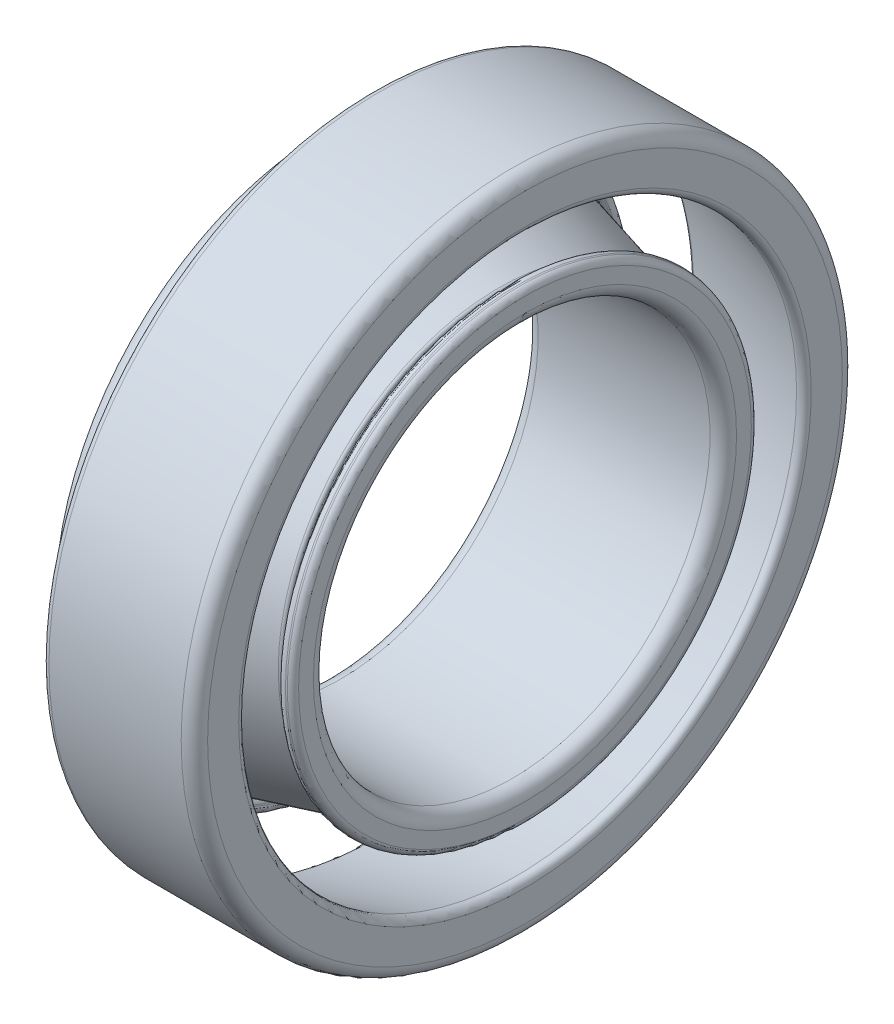
SolidWorks part; units mm, degrees
ref_plane "Front Plane" through (0, 0, 0) normal (0, 0, 1) x (1, 0, 0)
ref_plane "Top Plane" through (0, 0, 0) normal (0, 1, 0) x (1, 0, 0)
ref_plane "Right Plane" through (0, 0, 0) normal (1, 0, 0) x (0, 0, -1)
sketch "Sketch1" plane through (0, 0, 0) normal (0, 0, 1) x (1, 0, 0)
  line L0 (0, 0) -> (105.028, 0) construction
  line L1 (0, 48) -> (0, 43.2987)
  line L2 (-1.2522, 42.3311) -> (-22.2522, 47.8051)
  line L3 (-23, 49) -> (-23, 48.7727)
  line L4 (-22, 50) -> (-2, 50)
  line L5 (-11.7522, 45.0681) -> (-32.0851, -32.935) construction
  line L6 (-24.2703, 38.651) -> (-3.9596, 33.3567)
  line L7 (-2.2344, 34.3685) -> (-2.1876, 34.5483)
  line L8 (-0.9677, 35.2637) -> (-0.7478, 35.2064)
  line L9 (0, 34.2387) -> (0, 32)
  line L10 (-2, 30) -> (-28, 30)
  line L11 (-30, 32) -> (-30, 40.2433)
  line L12 (-27.4955, 42.1786) -> (-25.9506, 41.7759)
  line L13 (-25.2352, 40.556) -> (-25.2821, 40.3762)
  arc A0 (0, 48) -> (-2, 50) centre (-2, 48) ccw
  arc A1 (-23, 48.7727) -> (-22.2522, 47.8051) centre (-22, 48.7727) ccw
  arc A2 (0, 43.2987) -> (-1.2522, 42.3311) centre (-1, 43.2987) cw
  arc A3 (-23, 49) -> (-22, 50) centre (-22, 49) cw
  arc A4 (-25.7235, 40.0042) -> (-24.8106, 38.4474) centre (-25.6388, 39.0078) ccw
  arc A5 (-3.5876, 32.9153) -> (-2.0308, 33.8282) centre (-2.5912, 33) ccw
  arc A6 (0, 32) -> (-2, 30) centre (-2, 32) cw
  arc A7 (-28, 30) -> (-30, 32) centre (-28, 32) cw
  arc A8 (-30, 40.2433) -> (-27.4955, 42.1786) centre (-28, 40.2433) cw
  arc A9 (-0.7478, 35.2064) -> (0, 34.2387) centre (-1, 34.2387) cw
  arc A10 (-2.1876, 34.5483) -> (-0.9677, 35.2637) centre (-1.2199, 34.296) cw
  arc A11 (-25.9506, 41.7759) -> (-25.2352, 40.556) centre (-26.2029, 40.8083) cw
  arc A12 (-2.0308, 33.8282) -> (-2.2344, 34.3685) centre (-1.7506, 34.2424) cw
  arc A13 (-3.5876, 32.9153) -> (-3.9596, 33.3567) centre (-4.0858, 32.8729) ccw
  arc A14 (-24.8106, 38.4474) -> (-24.2703, 38.651) centre (-24.3964, 38.1672) cw
  arc A15 (-25.7235, 40.0042) -> (-25.2821, 40.3762) centre (-25.7659, 40.5024) ccw
  point P9 (-23.5, 0)
  point P10 (0, 0)
  point P13 (0, 50)
  point P16 (-23, 50)
  point P21 (-23, 48)
  point P31 (-14.115, 36.0039)
  point P35 (-23, 50)
  point P38 (0, 30)
  point P41 (-30, 30)
  point P46 (0, 35.0115)
  point P49 (-1.9353, 35.5159)
  point P54 (-2.3389, 33.9677)
  dimension "D5" = 2
  dimension "D6" = 1
  dimension "D9" = 2
  dimension "D10" = 2
  dimension "D15" = 1
  dimension "D16" = 1
  dimension "D17" = 2
  dimension "D18" = 1
  dimension "D19" = 0.5
  dimension "D1" = 23
  dimension "D2" = 50
  dimension "D3" = 23.5
  dimension "D4" = 48
  dimension "D7" = 1.6
  dimension "D8" = 2
  dimension "D11" = 30
  dimension "D12" = 30
  dimension "D13" = 30
  dimension "D14" = 33
revolve "Revolve1" add sketch "Sketch1" angle 360 about L0
